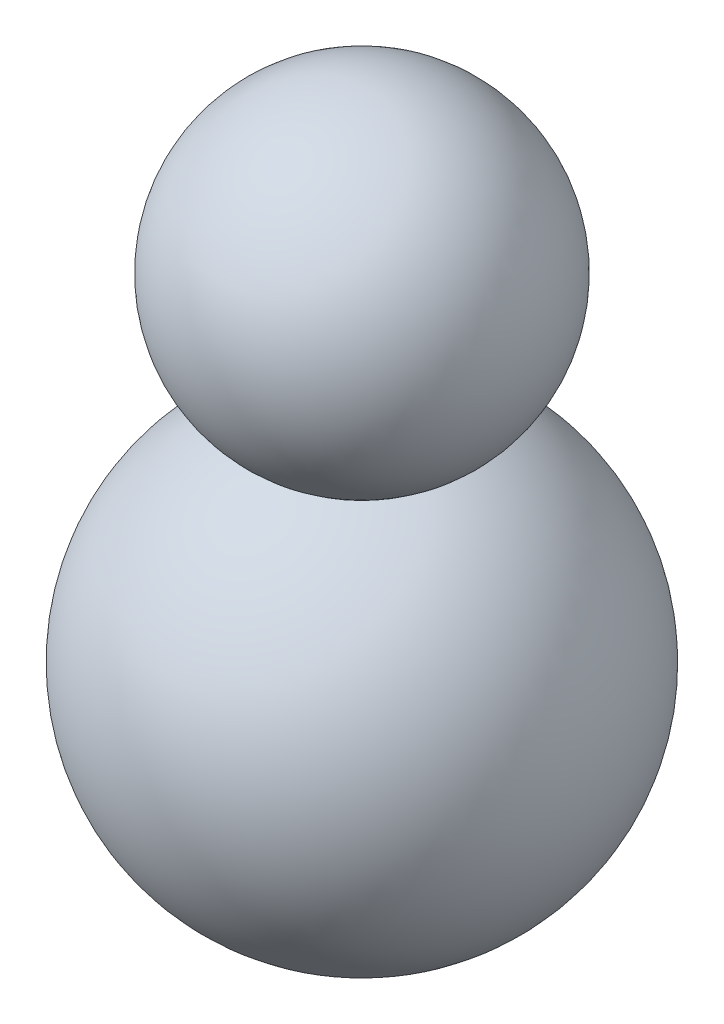
SolidWorks part; units mm, degrees
ref_plane "前视基准面" through (0, 0, 0) normal (0, 0, 1) x (1, 0, 0)
ref_plane "上视基准面" through (0, 0, 0) normal (0, 1, 0) x (1, 0, 0)
ref_plane "右视基准面" through (0, 0, 0) normal (1, 0, 0) x (0, 0, -1)
other "Configuration Table"
sketch "草图1" plane through (0, 0, 0) normal (0, 0, 1) x (1, 0, 0)
  line L0 (0, 0) -> (0, 25)
  arc A0 (0, 25) -> (0, 0) centre (0, 12.5) cw
  dimension "D1" = 25
revolve "旋转-薄壁3" add sketch "草图1" angle 360 about L0
sketch "草图4" plane through (0, 0, 0) normal (0, 0, 1) x (1, 0, 0)
  line L0 (0, 22.3609) -> (0, 40.3609)
  arc A0 (0, 40.3609) -> (0, 22.3609) centre (0, 31.3609) ccw
  point P6 (0, 21.2784)
  point P7 (17.2341, 23.9485)
  dimension "D1" = 18
revolve "旋转-薄壁4" add sketch "草图4" angle 360 about L0 wall 3
ref_plane "基准面1" through (0, 0, 0) normal (0, 0, 1) x (1, 0, 0)
sketch "草图5" plane through (0, 0, 0) normal (0, 0, 1) x (1, 0, 0)
  line L0 (0, 0) -> (0, 42.0153) construction
  line L1 (-1.8856, 35.3537) -> (-2.9914, 34.5773)
  line L2 (-2.9914, 34.5773) -> (-1.8187, 34.0828)
  line L3 (-1.3947, 35.7552) -> (-1.6956, 35.7508)
  circle A0 centre (-3.9313, 33.8867) radius 0.418
  ellipse E0 centre (-3.5593, 34.5773) end of major axis (-3.5593, 32.3413) minor radius 1.7847 (-1.8856, 35.3537) -> (-4.6724, 36.3251) ccw
  ellipse E1 centre (-3.3942, 33.5496) end of major axis (-3.3942, 30.1583) minor radius 2.2328 (-1.6956, 35.7508) -> (-4.8851, 36.0741) ccw
  ellipse E2 centre (-3.9313, 35.4874) end of major axis (-3.9313, 34.7371) minor radius 0.5371
  ellipse E3 centre (-3.3942, 33.299) end of major axis (-3.797, 29.471) minor radius 2.3889 (-1.3947, 35.7552) -> (-4.6724, 36.3251) ccw
  ellipse E4 centre (-3.5593, 34.5773) end of major axis (-3.5593, 32.3413) minor radius 1.7847 (-4.8851, 36.0741) -> (-1.8187, 34.0828) ccw
  point P8 (0, 0)
  point P29 (-5.1002, 35.7375)
  point P33 (0, 0)
  point P35 (-5.2748, 35.3777)
  point P37 (0, 0)
  point P38 (0, 0)
  point P43 (0, 0)
